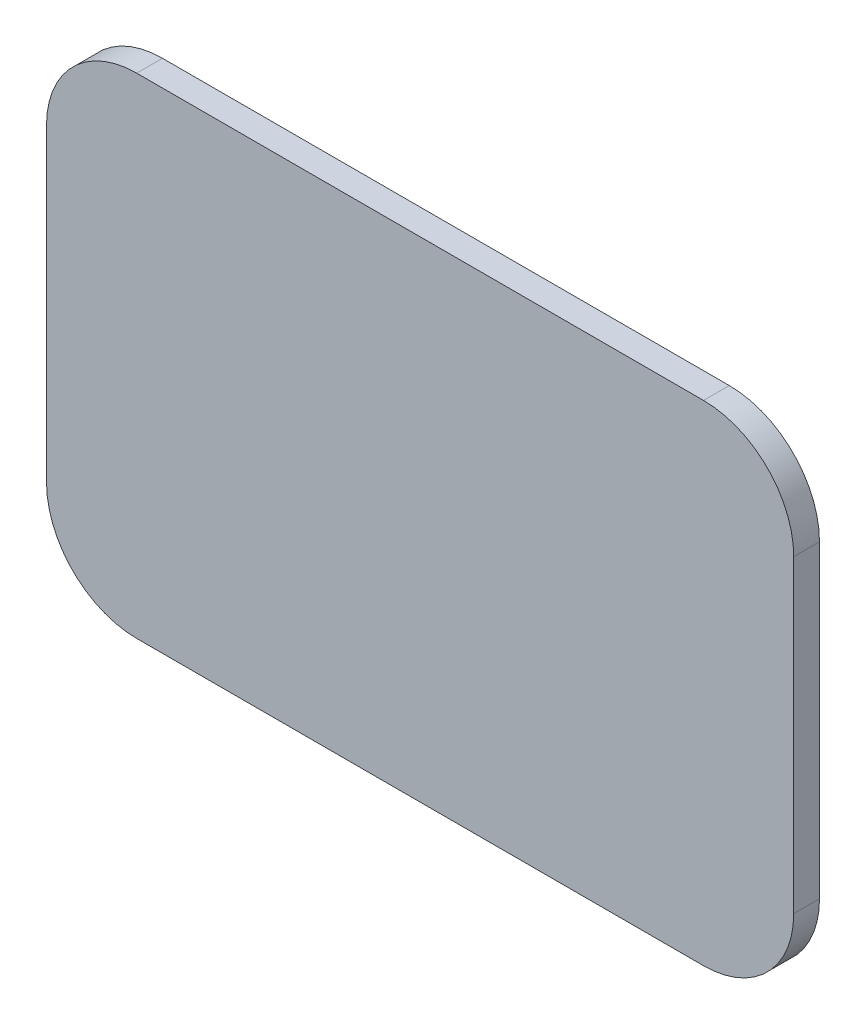
SolidWorks part; units mm, degrees
ref_plane "Front Plane" through (0, 0, 0) normal (0, 0, 1) x (1, 0, 0)
ref_plane "Top Plane" through (0, 0, 0) normal (0, 1, 0) x (1, 0, 0)
ref_plane "Right Plane" through (0, 0, 0) normal (1, 0, 0) x (0, 0, -1)
sketch "Sketch1" plane through (0, 0, 0) normal (0, 0, 1) x (1, 0, 0)
  line L0 (15, 0) -> (15.7, 0) construction
  line L1 (-11, -10) -> (11, -10)
  line L2 (-15, -6) -> (-15, 6)
  line L3 (-11, 10) -> (11, 10)
  line L4 (15, -6) -> (15, 6)
  line L5 (14.5, -6) -> (14.5, 6)
  line L6 (-11, 9.5) -> (11, 9.5)
  line L7 (-14.5, -6) -> (-14.5, 6)
  line L8 (-11, -9.5) -> (11, -9.5)
  arc A0 (15, 6) -> (11, 10) centre (11, 6) ccw
  arc A1 (-11, 10) -> (-15, 6) centre (-11, 6) ccw
  arc A2 (-15, -6) -> (-11, -10) centre (-11, -6) ccw
  arc A3 (11, -10) -> (15, -6) centre (11, -6) ccw
  arc A4 (11, -9.5) -> (14.5, -6) centre (11, -6) ccw
  arc A5 (14.5, 6) -> (11, 9.5) centre (11, 6) ccw
  arc A6 (-11, 9.5) -> (-14.5, 6) centre (-11, 6) ccw
  arc A7 (-14.5, -6) -> (-11, -9.5) centre (-11, -6) ccw
  point P0 (0, 0)
  point P4 (0, 0)
  point P6 (0, 0)
  point P7 (0, 0)
  point P9 (0, 0)
  point P10 (0, 0)
  point P11 (0, 0)
  dimension "D1" = 4
extrude "Boss-Extrude1" add sketch "Sketch1" along normal blind 1 contours L7 A7 L8 A4 L5 A5 L6 A6
